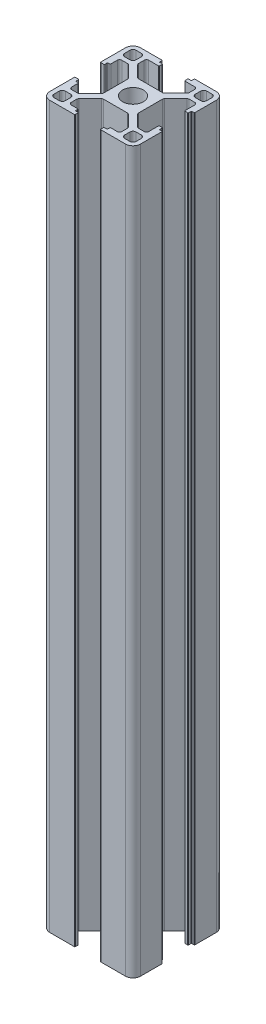
SolidWorks part; units mm, degrees
ref_plane "Front Plane" through (0, 0, 0) normal (0, 0, 1) x (1, 0, 0)
ref_plane "Top Plane" through (0, 0, 0) normal (0, 1, 0) x (1, 0, 0)
ref_plane "Right Plane" through (0, 0, 0) normal (1, 0, 0) x (0, 0, -1)
sketch "Sketch2" plane through (0, -1630.4411, 0) normal (0, 1, 0) x (1, 0, 0)
  line L4 (-1206.0668, -28.55) -> (-1204.3168, -28.55)
  line L5 (-1203.3168, -27.55) -> (-1203.3168, -25.8)
  line L6 (-1204.3168, -24.8) -> (-1206.0668, -24.8)
  line L7 (-1207.0668, -25.8) -> (-1207.0668, -27.55)
  line L8 (-1206.0668, -28.55) -> (-1204.3168, -28.55)
  line L9 (-1203.3168, -27.55) -> (-1203.3168, -25.8)
  line L10 (-1204.3168, -24.8) -> (-1206.0668, -24.8)
  line L11 (-1207.0668, -25.8) -> (-1207.0668, -27.55)
  line L12 (-1206.0668, -5.2) -> (-1204.3168, -5.2)
  line L13 (-1203.3168, -4.2) -> (-1203.3168, -2.45)
  line L14 (-1204.3168, -1.45) -> (-1206.0668, -1.45)
  line L15 (-1207.0668, -2.45) -> (-1207.0668, -4.2)
  line L16 (-1206.0668, -5.2) -> (-1204.3168, -5.2)
  line L17 (-1203.3168, -4.2) -> (-1203.3168, -2.45)
  line L18 (-1204.3168, -1.45) -> (-1206.0668, -1.45)
  line L19 (-1207.0668, -2.45) -> (-1207.0668, -4.2)
  line L20 (-1180.9668, -24.8) -> (-1182.7168, -24.8)
  line L21 (-1183.7168, -25.8) -> (-1183.7168, -27.55)
  line L22 (-1182.7168, -28.55) -> (-1180.9668, -28.55)
  line L23 (-1179.9668, -27.55) -> (-1179.9668, -25.8)
  line L24 (-1180.9668, -24.8) -> (-1182.7168, -24.8)
  line L25 (-1183.7168, -25.8) -> (-1183.7168, -27.55)
  line L26 (-1182.7168, -28.55) -> (-1180.9668, -28.55)
  line L27 (-1179.9668, -27.55) -> (-1179.9668, -25.8)
  line L28 (-1182.7168, -5.2) -> (-1180.9668, -5.2)
  line L29 (-1179.9668, -4.2) -> (-1179.9668, -2.45)
  line L30 (-1180.9668, -1.45) -> (-1182.7168, -1.45)
  line L31 (-1183.7168, -2.45) -> (-1183.7168, -4.2)
  line L32 (-1182.7168, -5.2) -> (-1180.9668, -5.2)
  line L33 (-1179.9668, -4.2) -> (-1179.9668, -2.45)
  line L34 (-1180.9668, -1.45) -> (-1182.7168, -1.45)
  line L35 (-1183.7168, -2.45) -> (-1183.7168, -4.2)
  line L60 (-1199.0168, 0) -> (-1206.0168, 0)
  line L61 (-1198.8168, -0.8) -> (-1198.8168, -0.2)
  line L62 (-1197.9168, -1) -> (-1198.6168, -1)
  line L63 (-1197.7168, -2) -> (-1197.7168, -1.2)
  line L64 (-1201.1168, -2.2) -> (-1197.9168, -2.2)
  line L65 (-1201.8668, -4.7837) -> (-1201.8668, -2.95)
  line L66 (-1197.9808, -8.9803) -> (-1201.6471, -5.314)
  line L67 (-1189.5831, -9.2) -> (-1197.4505, -9.2)
  line L68 (-1185.3865, -5.314) -> (-1189.0528, -8.9803)
  line L69 (-1185.1668, -2.95) -> (-1185.1668, -4.7837)
  line L70 (-1189.1168, -2.2) -> (-1185.9168, -2.2)
  line L71 (-1189.3168, -1.2) -> (-1189.3168, -2)
  line L72 (-1188.4168, -1) -> (-1189.1168, -1)
  line L73 (-1188.2168, -0.2) -> (-1188.2168, -0.8)
  line L74 (-1181.0168, 0) -> (-1188.0168, 0)
  line L75 (-1178.5168, -9.5) -> (-1178.5168, -2.5)
  line L76 (-1179.3168, -9.7) -> (-1178.7168, -9.7)
  line L77 (-1179.5168, -10.6) -> (-1179.5168, -9.9)
  line L78 (-1180.5168, -10.8) -> (-1179.7168, -10.8)
  line L79 (-1180.7168, -7.4) -> (-1180.7168, -10.6)
  line L80 (-1183.3005, -6.65) -> (-1181.4668, -6.65)
  line L81 (-1187.4971, -10.536) -> (-1183.8308, -6.8697)
  line L82 (-1187.7168, -18.9337) -> (-1187.7168, -11.0663)
  line L83 (-1183.8308, -23.1303) -> (-1187.4971, -19.464)
  line L84 (-1181.4668, -23.35) -> (-1183.3005, -23.35)
  line L85 (-1180.7168, -19.4) -> (-1180.7168, -22.6)
  line L86 (-1179.7168, -19.2) -> (-1180.5168, -19.2)
  line L87 (-1179.5168, -20.1) -> (-1179.5168, -19.4)
  line L88 (-1178.7168, -20.3) -> (-1179.3168, -20.3)
  line L89 (-1178.5168, -27.5) -> (-1178.5168, -20.5)
  line L90 (-1189.1168, -30) -> (-1181.0168, -30)
  line L91 (-1189.3168, -29) -> (-1189.3168, -29.8)
  line L92 (-1188.4168, -28.8) -> (-1189.1168, -28.8)
  line L93 (-1188.2168, -28) -> (-1188.2168, -28.6)
  line L94 (-1185.9168, -27.8) -> (-1188.0168, -27.8)
  line L95 (-1185.1668, -25.2163) -> (-1185.1668, -27.05)
  line L96 (-1189.0528, -21.0197) -> (-1185.3865, -24.686)
  line L97 (-1197.4505, -20.8) -> (-1189.5831, -20.8)
  line L98 (-1201.6471, -24.686) -> (-1197.9808, -21.0197)
  line L99 (-1201.8668, -27.05) -> (-1201.8668, -25.2163)
  line L100 (-1199.0168, -27.8) -> (-1201.1168, -27.8)
  line L101 (-1198.8168, -28.6) -> (-1198.8168, -28)
  line L102 (-1197.9168, -28.8) -> (-1198.6168, -28.8)
  line L103 (-1197.7168, -29.8) -> (-1197.7168, -29)
  line L104 (-1206.0168, -30) -> (-1197.9168, -30)
  line L105 (-1208.5168, -19.4) -> (-1208.5168, -27.5)
  line L106 (-1207.3844, -19.2) -> (-1208.3168, -19.2)
  line L107 (-1207.1844, -20.1) -> (-1207.1844, -19.4)
  line L108 (-1206.3844, -20.3) -> (-1206.9844, -20.3)
  line L109 (-1206.1844, -22.6) -> (-1206.1844, -20.5)
  line L110 (-1203.6007, -23.35) -> (-1205.4344, -23.35)
  line L111 (-1199.404, -19.464) -> (-1203.0703, -23.1303)
  line L112 (-1199.1844, -11.0663) -> (-1199.1844, -18.9337)
  line L113 (-1203.0703, -6.8697) -> (-1199.404, -10.536)
  line L114 (-1205.5668, -6.65) -> (-1203.6007, -6.65)
  line L115 (-1206.3168, -9.5) -> (-1206.3168, -7.4)
  line L116 (-1206.9844, -9.7) -> (-1206.5168, -9.7)
  line L117 (-1207.1844, -10.6) -> (-1207.1844, -9.9)
  line L118 (-1208.3168, -10.8) -> (-1207.3844, -10.8)
  line L119 (-1208.5168, -2.5) -> (-1208.5168, -10.6)
  line L120 (-1199.0168, 0) -> (-1206.0168, 0)
  line L121 (-1198.8168, -0.8) -> (-1198.8168, -0.2)
  line L122 (-1197.9168, -1) -> (-1198.6168, -1)
  line L123 (-1197.7168, -2) -> (-1197.7168, -1.2)
  line L124 (-1201.1168, -2.2) -> (-1197.9168, -2.2)
  line L125 (-1201.8668, -4.7837) -> (-1201.8668, -2.95)
  line L126 (-1197.9808, -8.9803) -> (-1201.6471, -5.314)
  line L127 (-1189.5831, -9.2) -> (-1197.4505, -9.2)
  line L128 (-1185.3865, -5.314) -> (-1189.0528, -8.9803)
  line L129 (-1185.1668, -2.95) -> (-1185.1668, -4.7837)
  line L130 (-1189.1168, -2.2) -> (-1185.9168, -2.2)
  line L131 (-1189.3168, -1.2) -> (-1189.3168, -2)
  line L132 (-1188.4168, -1) -> (-1189.1168, -1)
  line L133 (-1188.2168, -0.2) -> (-1188.2168, -0.8)
  line L134 (-1181.0168, 0) -> (-1188.0168, 0)
  line L135 (-1178.5168, -9.5) -> (-1178.5168, -2.5)
  line L136 (-1179.3168, -9.7) -> (-1178.7168, -9.7)
  line L137 (-1179.5168, -10.6) -> (-1179.5168, -9.9)
  line L138 (-1180.5168, -10.8) -> (-1179.7168, -10.8)
  line L139 (-1180.7168, -7.4) -> (-1180.7168, -10.6)
  line L140 (-1183.3005, -6.65) -> (-1181.4668, -6.65)
  line L141 (-1187.4971, -10.536) -> (-1183.8308, -6.8697)
  line L142 (-1187.7168, -18.9337) -> (-1187.7168, -11.0663)
  line L143 (-1183.8308, -23.1303) -> (-1187.4971, -19.464)
  line L144 (-1181.4668, -23.35) -> (-1183.3005, -23.35)
  line L145 (-1180.7168, -19.4) -> (-1180.7168, -22.6)
  line L146 (-1179.7168, -19.2) -> (-1180.5168, -19.2)
  line L147 (-1179.5168, -20.1) -> (-1179.5168, -19.4)
  line L148 (-1178.7168, -20.3) -> (-1179.3168, -20.3)
  line L149 (-1178.5168, -27.5) -> (-1178.5168, -20.5)
  line L150 (-1189.1168, -30) -> (-1181.0168, -30)
  line L151 (-1189.3168, -29) -> (-1189.3168, -29.8)
  line L152 (-1188.4168, -28.8) -> (-1189.1168, -28.8)
  line L153 (-1188.2168, -28) -> (-1188.2168, -28.6)
  line L154 (-1185.9168, -27.8) -> (-1188.0168, -27.8)
  line L155 (-1185.1668, -25.2163) -> (-1185.1668, -27.05)
  line L156 (-1189.0528, -21.0197) -> (-1185.3865, -24.686)
  line L157 (-1197.4505, -20.8) -> (-1189.5831, -20.8)
  line L158 (-1201.6471, -24.686) -> (-1197.9808, -21.0197)
  line L159 (-1201.8668, -27.05) -> (-1201.8668, -25.2163)
  line L160 (-1199.0168, -27.8) -> (-1201.1168, -27.8)
  line L161 (-1198.8168, -28.6) -> (-1198.8168, -28)
  line L162 (-1197.9168, -28.8) -> (-1198.6168, -28.8)
  line L163 (-1197.7168, -29.8) -> (-1197.7168, -29)
  line L164 (-1206.0168, -30) -> (-1197.9168, -30)
  line L165 (-1208.5168, -19.4) -> (-1208.5168, -27.5)
  line L166 (-1207.3844, -19.2) -> (-1208.3168, -19.2)
  line L167 (-1207.1844, -20.1) -> (-1207.1844, -19.4)
  line L168 (-1206.3844, -20.3) -> (-1206.9844, -20.3)
  line L169 (-1206.1844, -22.6) -> (-1206.1844, -20.5)
  line L170 (-1203.6007, -23.35) -> (-1205.4344, -23.35)
  line L171 (-1199.404, -19.464) -> (-1203.0703, -23.1303)
  line L172 (-1199.1844, -11.0663) -> (-1199.1844, -18.9337)
  line L173 (-1203.0703, -6.8697) -> (-1199.404, -10.536)
  line L174 (-1205.5668, -6.65) -> (-1203.6007, -6.65)
  line L175 (-1206.3168, -9.5) -> (-1206.3168, -7.4)
  line L176 (-1206.9844, -9.7) -> (-1206.5168, -9.7)
  line L177 (-1207.1844, -10.6) -> (-1207.1844, -9.9)
  line L178 (-1208.3168, -10.8) -> (-1207.3844, -10.8)
  line L179 (-1208.5168, -2.5) -> (-1208.5168, -10.6)
  arc A2 (-1193.5168, -11.6) -> (-1193.5168, -18.4) centre (-1193.5168, -15) ccw
  arc A3 (-1193.5168, -18.4) -> (-1193.5168, -11.6) centre (-1193.5168, -15) ccw
  arc A4 (-1207.0668, -27.55) -> (-1206.0668, -28.55) centre (-1206.0668, -27.55) ccw
  arc A5 (-1204.3168, -28.55) -> (-1203.3168, -27.55) centre (-1204.3168, -27.55) ccw
  arc A6 (-1203.3168, -25.8) -> (-1204.3168, -24.8) centre (-1204.3168, -25.8) ccw
  arc A7 (-1206.0668, -24.8) -> (-1207.0668, -25.8) centre (-1206.0668, -25.8) ccw
  arc A8 (-1207.0668, -27.55) -> (-1206.0668, -28.55) centre (-1206.0668, -27.55) ccw
  arc A9 (-1204.3168, -28.55) -> (-1203.3168, -27.55) centre (-1204.3168, -27.55) ccw
  arc A10 (-1203.3168, -25.8) -> (-1204.3168, -24.8) centre (-1204.3168, -25.8) ccw
  arc A11 (-1206.0668, -24.8) -> (-1207.0668, -25.8) centre (-1206.0668, -25.8) ccw
  arc A12 (-1207.0668, -4.2) -> (-1206.0668, -5.2) centre (-1206.0668, -4.2) ccw
  arc A13 (-1204.3168, -5.2) -> (-1203.3168, -4.2) centre (-1204.3168, -4.2) ccw
  arc A14 (-1203.3168, -2.45) -> (-1204.3168, -1.45) centre (-1204.3168, -2.45) ccw
  arc A15 (-1206.0668, -1.45) -> (-1207.0668, -2.45) centre (-1206.0668, -2.45) ccw
  arc A16 (-1207.0668, -4.2) -> (-1206.0668, -5.2) centre (-1206.0668, -4.2) ccw
  arc A17 (-1204.3168, -5.2) -> (-1203.3168, -4.2) centre (-1204.3168, -4.2) ccw
  arc A18 (-1203.3168, -2.45) -> (-1204.3168, -1.45) centre (-1204.3168, -2.45) ccw
  arc A19 (-1206.0668, -1.45) -> (-1207.0668, -2.45) centre (-1206.0668, -2.45) ccw
  arc A20 (-1193.5168, -11.6) -> (-1193.5168, -18.4) centre (-1193.5168, -15) ccw
  arc A21 (-1193.5168, -18.4) -> (-1193.5168, -11.6) centre (-1193.5168, -15) ccw
  arc A24 (-1179.9668, -25.8) -> (-1180.9668, -24.8) centre (-1180.9668, -25.8) ccw
  arc A25 (-1182.7168, -24.8) -> (-1183.7168, -25.8) centre (-1182.7168, -25.8) ccw
  arc A26 (-1183.7168, -27.55) -> (-1182.7168, -28.55) centre (-1182.7168, -27.55) ccw
  arc A27 (-1180.9668, -28.55) -> (-1179.9668, -27.55) centre (-1180.9668, -27.55) ccw
  arc A28 (-1179.9668, -25.8) -> (-1180.9668, -24.8) centre (-1180.9668, -25.8) ccw
  arc A29 (-1182.7168, -24.8) -> (-1183.7168, -25.8) centre (-1182.7168, -25.8) ccw
  arc A30 (-1183.7168, -27.55) -> (-1182.7168, -28.55) centre (-1182.7168, -27.55) ccw
  arc A31 (-1180.9668, -28.55) -> (-1179.9668, -27.55) centre (-1180.9668, -27.55) ccw
  arc A32 (-1183.7168, -4.2) -> (-1182.7168, -5.2) centre (-1182.7168, -4.2) ccw
  arc A33 (-1180.9668, -5.2) -> (-1179.9668, -4.2) centre (-1180.9668, -4.2) ccw
  arc A34 (-1179.9668, -2.45) -> (-1180.9668, -1.45) centre (-1180.9668, -2.45) ccw
  arc A35 (-1182.7168, -1.45) -> (-1183.7168, -2.45) centre (-1182.7168, -2.45) ccw
  arc A36 (-1183.7168, -4.2) -> (-1182.7168, -5.2) centre (-1182.7168, -4.2) ccw
  arc A37 (-1180.9668, -5.2) -> (-1179.9668, -4.2) centre (-1180.9668, -4.2) ccw
  arc A38 (-1179.9668, -2.45) -> (-1180.9668, -1.45) centre (-1180.9668, -2.45) ccw
  arc A39 (-1182.7168, -1.45) -> (-1183.7168, -2.45) centre (-1182.7168, -2.45) ccw
  arc A60 (-1206.0168, 0) -> (-1208.5168, -2.5) centre (-1206.0168, -2.5) ccw
  arc A61 (-1198.8168, -0.2) -> (-1199.0168, 0) centre (-1199.0168, -0.2) ccw
  arc A62 (-1198.8168, -0.8) -> (-1198.6168, -1) centre (-1198.6168, -0.8) ccw
  arc A63 (-1197.7168, -1.2) -> (-1197.9168, -1) centre (-1197.9168, -1.2) ccw
  arc A64 (-1197.9168, -2.2) -> (-1197.7168, -2) centre (-1197.9168, -2) ccw
  arc A65 (-1201.1168, -2.2) -> (-1201.8668, -2.95) centre (-1201.1168, -2.95) ccw
  arc A66 (-1201.8668, -4.7837) -> (-1201.6471, -5.314) centre (-1201.1168, -4.7837) ccw
  arc A67 (-1197.9808, -8.9803) -> (-1197.4505, -9.2) centre (-1197.4505, -8.45) ccw
  arc A68 (-1189.5831, -9.2) -> (-1189.0528, -8.9803) centre (-1189.5831, -8.45) ccw
  arc A69 (-1185.3865, -5.314) -> (-1185.1668, -4.7837) centre (-1185.9168, -4.7837) ccw
  arc A70 (-1185.1668, -2.95) -> (-1185.9168, -2.2) centre (-1185.9168, -2.95) ccw
  arc A71 (-1189.3168, -2) -> (-1189.1168, -2.2) centre (-1189.1168, -2) ccw
  arc A72 (-1189.1168, -1) -> (-1189.3168, -1.2) centre (-1189.1168, -1.2) ccw
  arc A73 (-1188.4168, -1) -> (-1188.2168, -0.8) centre (-1188.4168, -0.8) ccw
  arc A74 (-1188.0168, 0) -> (-1188.2168, -0.2) centre (-1188.0168, -0.2) ccw
  arc A75 (-1178.5168, -2.5) -> (-1181.0168, 0) centre (-1181.0168, -2.5) ccw
  arc A76 (-1178.7168, -9.7) -> (-1178.5168, -9.5) centre (-1178.7168, -9.5) ccw
  arc A77 (-1179.3168, -9.7) -> (-1179.5168, -9.9) centre (-1179.3168, -9.9) ccw
  arc A78 (-1179.7168, -10.8) -> (-1179.5168, -10.6) centre (-1179.7168, -10.6) ccw
  arc A79 (-1180.7168, -10.6) -> (-1180.5168, -10.8) centre (-1180.5168, -10.6) ccw
  arc A80 (-1180.7168, -7.4) -> (-1181.4668, -6.65) centre (-1181.4668, -7.4) ccw
  arc A81 (-1183.3005, -6.65) -> (-1183.8308, -6.8697) centre (-1183.3005, -7.4) ccw
  arc A82 (-1187.4971, -10.536) -> (-1187.7168, -11.0663) centre (-1186.9668, -11.0663) ccw
  arc A83 (-1187.7168, -18.9337) -> (-1187.4971, -19.464) centre (-1186.9668, -18.9337) ccw
  arc A84 (-1183.8308, -23.1303) -> (-1183.3005, -23.35) centre (-1183.3005, -22.6) ccw
  arc A85 (-1181.4668, -23.35) -> (-1180.7168, -22.6) centre (-1181.4668, -22.6) ccw
  arc A86 (-1180.5168, -19.2) -> (-1180.7168, -19.4) centre (-1180.5168, -19.4) ccw
  arc A87 (-1179.5168, -19.4) -> (-1179.7168, -19.2) centre (-1179.7168, -19.4) ccw
  arc A88 (-1179.5168, -20.1) -> (-1179.3168, -20.3) centre (-1179.3168, -20.1) ccw
  arc A89 (-1178.5168, -20.5) -> (-1178.7168, -20.3) centre (-1178.7168, -20.5) ccw
  arc A90 (-1181.0168, -30) -> (-1178.5168, -27.5) centre (-1181.0168, -27.5) ccw
  arc A91 (-1189.3168, -29.8) -> (-1189.1168, -30) centre (-1189.1168, -29.8) ccw
  arc A92 (-1189.1168, -28.8) -> (-1189.3168, -29) centre (-1189.1168, -29) ccw
  arc A93 (-1188.4168, -28.8) -> (-1188.2168, -28.6) centre (-1188.4168, -28.6) ccw
  arc A94 (-1188.0168, -27.8) -> (-1188.2168, -28) centre (-1188.0168, -28) ccw
  arc A95 (-1185.9168, -27.8) -> (-1185.1668, -27.05) centre (-1185.9168, -27.05) ccw
  arc A96 (-1185.1668, -25.2163) -> (-1185.3865, -24.686) centre (-1185.9168, -25.2163) ccw
  arc A97 (-1189.0528, -21.0197) -> (-1189.5831, -20.8) centre (-1189.5831, -21.55) ccw
  arc A98 (-1197.4505, -20.8) -> (-1197.9808, -21.0197) centre (-1197.4505, -21.55) ccw
  arc A99 (-1201.6471, -24.686) -> (-1201.8668, -25.2163) centre (-1201.1168, -25.2163) ccw
  arc A100 (-1201.8668, -27.05) -> (-1201.1168, -27.8) centre (-1201.1168, -27.05) ccw
  arc A101 (-1198.8168, -28) -> (-1199.0168, -27.8) centre (-1199.0168, -28) ccw
  arc A102 (-1198.8168, -28.6) -> (-1198.6168, -28.8) centre (-1198.6168, -28.6) ccw
  arc A103 (-1197.7168, -29) -> (-1197.9168, -28.8) centre (-1197.9168, -29) ccw
  arc A104 (-1197.9168, -30) -> (-1197.7168, -29.8) centre (-1197.9168, -29.8) ccw
  arc A105 (-1208.5168, -27.5) -> (-1206.0168, -30) centre (-1206.0168, -27.5) ccw
  arc A106 (-1208.3168, -19.2) -> (-1208.5168, -19.4) centre (-1208.3168, -19.4) ccw
  arc A107 (-1207.1844, -19.4) -> (-1207.3844, -19.2) centre (-1207.3844, -19.4) ccw
  arc A108 (-1207.1844, -20.1) -> (-1206.9844, -20.3) centre (-1206.9844, -20.1) ccw
  arc A109 (-1206.1844, -20.5) -> (-1206.3844, -20.3) centre (-1206.3844, -20.5) ccw
  arc A110 (-1206.1844, -22.6) -> (-1205.4344, -23.35) centre (-1205.4344, -22.6) ccw
  arc A111 (-1203.6007, -23.35) -> (-1203.0703, -23.1303) centre (-1203.6007, -22.6) ccw
  arc A112 (-1199.404, -19.464) -> (-1199.1844, -18.9337) centre (-1199.9344, -18.9337) ccw
  arc A113 (-1199.1844, -11.0663) -> (-1199.404, -10.536) centre (-1199.9344, -11.0663) ccw
  arc A114 (-1203.0703, -6.8697) -> (-1203.6007, -6.65) centre (-1203.6007, -7.4) ccw
  arc A115 (-1205.5668, -6.65) -> (-1206.3168, -7.4) centre (-1205.5668, -7.4) ccw
  arc A116 (-1206.5168, -9.7) -> (-1206.3168, -9.5) centre (-1206.5168, -9.5) ccw
  arc A117 (-1206.9844, -9.7) -> (-1207.1844, -9.9) centre (-1206.9844, -9.9) ccw
  arc A118 (-1207.3844, -10.8) -> (-1207.1844, -10.6) centre (-1207.3844, -10.6) ccw
  arc A119 (-1208.5168, -10.6) -> (-1208.3168, -10.8) centre (-1208.3168, -10.6) ccw
  arc A120 (-1206.0168, 0) -> (-1208.5168, -2.5) centre (-1206.0168, -2.5) ccw
  arc A121 (-1198.8168, -0.2) -> (-1199.0168, 0) centre (-1199.0168, -0.2) ccw
  arc A122 (-1198.8168, -0.8) -> (-1198.6168, -1) centre (-1198.6168, -0.8) ccw
  arc A123 (-1197.7168, -1.2) -> (-1197.9168, -1) centre (-1197.9168, -1.2) ccw
  arc A124 (-1197.9168, -2.2) -> (-1197.7168, -2) centre (-1197.9168, -2) ccw
  arc A125 (-1201.1168, -2.2) -> (-1201.8668, -2.95) centre (-1201.1168, -2.95) ccw
  arc A126 (-1201.8668, -4.7837) -> (-1201.6471, -5.314) centre (-1201.1168, -4.7837) ccw
  arc A127 (-1197.9808, -8.9803) -> (-1197.4505, -9.2) centre (-1197.4505, -8.45) ccw
  arc A128 (-1189.5831, -9.2) -> (-1189.0528, -8.9803) centre (-1189.5831, -8.45) ccw
  arc A129 (-1185.3865, -5.314) -> (-1185.1668, -4.7837) centre (-1185.9168, -4.7837) ccw
  arc A130 (-1185.1668, -2.95) -> (-1185.9168, -2.2) centre (-1185.9168, -2.95) ccw
  arc A131 (-1189.3168, -2) -> (-1189.1168, -2.2) centre (-1189.1168, -2) ccw
  arc A132 (-1189.1168, -1) -> (-1189.3168, -1.2) centre (-1189.1168, -1.2) ccw
  arc A133 (-1188.4168, -1) -> (-1188.2168, -0.8) centre (-1188.4168, -0.8) ccw
  arc A134 (-1188.0168, 0) -> (-1188.2168, -0.2) centre (-1188.0168, -0.2) ccw
  arc A135 (-1178.5168, -2.5) -> (-1181.0168, 0) centre (-1181.0168, -2.5) ccw
  arc A136 (-1178.7168, -9.7) -> (-1178.5168, -9.5) centre (-1178.7168, -9.5) ccw
  arc A137 (-1179.3168, -9.7) -> (-1179.5168, -9.9) centre (-1179.3168, -9.9) ccw
  arc A138 (-1179.7168, -10.8) -> (-1179.5168, -10.6) centre (-1179.7168, -10.6) ccw
  arc A139 (-1180.7168, -10.6) -> (-1180.5168, -10.8) centre (-1180.5168, -10.6) ccw
  arc A140 (-1180.7168, -7.4) -> (-1181.4668, -6.65) centre (-1181.4668, -7.4) ccw
  arc A141 (-1183.3005, -6.65) -> (-1183.8308, -6.8697) centre (-1183.3005, -7.4) ccw
  arc A142 (-1187.4971, -10.536) -> (-1187.7168, -11.0663) centre (-1186.9668, -11.0663) ccw
  arc A143 (-1187.7168, -18.9337) -> (-1187.4971, -19.464) centre (-1186.9668, -18.9337) ccw
  arc A144 (-1183.8308, -23.1303) -> (-1183.3005, -23.35) centre (-1183.3005, -22.6) ccw
  arc A145 (-1181.4668, -23.35) -> (-1180.7168, -22.6) centre (-1181.4668, -22.6) ccw
  arc A146 (-1180.5168, -19.2) -> (-1180.7168, -19.4) centre (-1180.5168, -19.4) ccw
  arc A147 (-1179.5168, -19.4) -> (-1179.7168, -19.2) centre (-1179.7168, -19.4) ccw
  arc A148 (-1179.5168, -20.1) -> (-1179.3168, -20.3) centre (-1179.3168, -20.1) ccw
  arc A149 (-1178.5168, -20.5) -> (-1178.7168, -20.3) centre (-1178.7168, -20.5) ccw
  arc A150 (-1181.0168, -30) -> (-1178.5168, -27.5) centre (-1181.0168, -27.5) ccw
  arc A151 (-1189.3168, -29.8) -> (-1189.1168, -30) centre (-1189.1168, -29.8) ccw
  arc A152 (-1189.1168, -28.8) -> (-1189.3168, -29) centre (-1189.1168, -29) ccw
  arc A153 (-1188.4168, -28.8) -> (-1188.2168, -28.6) centre (-1188.4168, -28.6) ccw
  arc A154 (-1188.0168, -27.8) -> (-1188.2168, -28) centre (-1188.0168, -28) ccw
  arc A155 (-1185.9168, -27.8) -> (-1185.1668, -27.05) centre (-1185.9168, -27.05) ccw
  arc A156 (-1185.1668, -25.2163) -> (-1185.3865, -24.686) centre (-1185.9168, -25.2163) ccw
  arc A157 (-1189.0528, -21.0197) -> (-1189.5831, -20.8) centre (-1189.5831, -21.55) ccw
  arc A158 (-1197.4505, -20.8) -> (-1197.9808, -21.0197) centre (-1197.4505, -21.55) ccw
  arc A159 (-1201.6471, -24.686) -> (-1201.8668, -25.2163) centre (-1201.1168, -25.2163) ccw
  arc A160 (-1201.8668, -27.05) -> (-1201.1168, -27.8) centre (-1201.1168, -27.05) ccw
  arc A161 (-1198.8168, -28) -> (-1199.0168, -27.8) centre (-1199.0168, -28) ccw
  arc A162 (-1198.8168, -28.6) -> (-1198.6168, -28.8) centre (-1198.6168, -28.6) ccw
  arc A163 (-1197.7168, -29) -> (-1197.9168, -28.8) centre (-1197.9168, -29) ccw
  arc A164 (-1197.9168, -30) -> (-1197.7168, -29.8) centre (-1197.9168, -29.8) ccw
  arc A165 (-1208.5168, -27.5) -> (-1206.0168, -30) centre (-1206.0168, -27.5) ccw
  arc A166 (-1208.3168, -19.2) -> (-1208.5168, -19.4) centre (-1208.3168, -19.4) ccw
  arc A167 (-1207.1844, -19.4) -> (-1207.3844, -19.2) centre (-1207.3844, -19.4) ccw
  arc A168 (-1207.1844, -20.1) -> (-1206.9844, -20.3) centre (-1206.9844, -20.1) ccw
  arc A169 (-1206.1844, -20.5) -> (-1206.3844, -20.3) centre (-1206.3844, -20.5) ccw
  arc A170 (-1206.1844, -22.6) -> (-1205.4344, -23.35) centre (-1205.4344, -22.6) ccw
  arc A171 (-1203.6007, -23.35) -> (-1203.0703, -23.1303) centre (-1203.6007, -22.6) ccw
  arc A172 (-1199.404, -19.464) -> (-1199.1844, -18.9337) centre (-1199.9344, -18.9337) ccw
  arc A173 (-1199.1844, -11.0663) -> (-1199.404, -10.536) centre (-1199.9344, -11.0663) ccw
  arc A174 (-1203.0703, -6.8697) -> (-1203.6007, -6.65) centre (-1203.6007, -7.4) ccw
  arc A175 (-1205.5668, -6.65) -> (-1206.3168, -7.4) centre (-1205.5668, -7.4) ccw
  arc A176 (-1206.5168, -9.7) -> (-1206.3168, -9.5) centre (-1206.5168, -9.5) ccw
  arc A177 (-1206.9844, -9.7) -> (-1207.1844, -9.9) centre (-1206.9844, -9.9) ccw
  arc A178 (-1207.3844, -10.8) -> (-1207.1844, -10.6) centre (-1207.3844, -10.6) ccw
  arc A179 (-1208.5168, -10.6) -> (-1208.3168, -10.8) centre (-1208.3168, -10.6) ccw
  dimension "D1" = 0
  dimension "D2" = 0
  dimension "D3" = 0
  dimension "D4" = 0
  dimension "D5" = 0
  dimension "D6" = 0
extrude "Boss-Extrude3" add sketch "Sketch2" along normal offset from surface (238 mm away) 1 from offset 1
